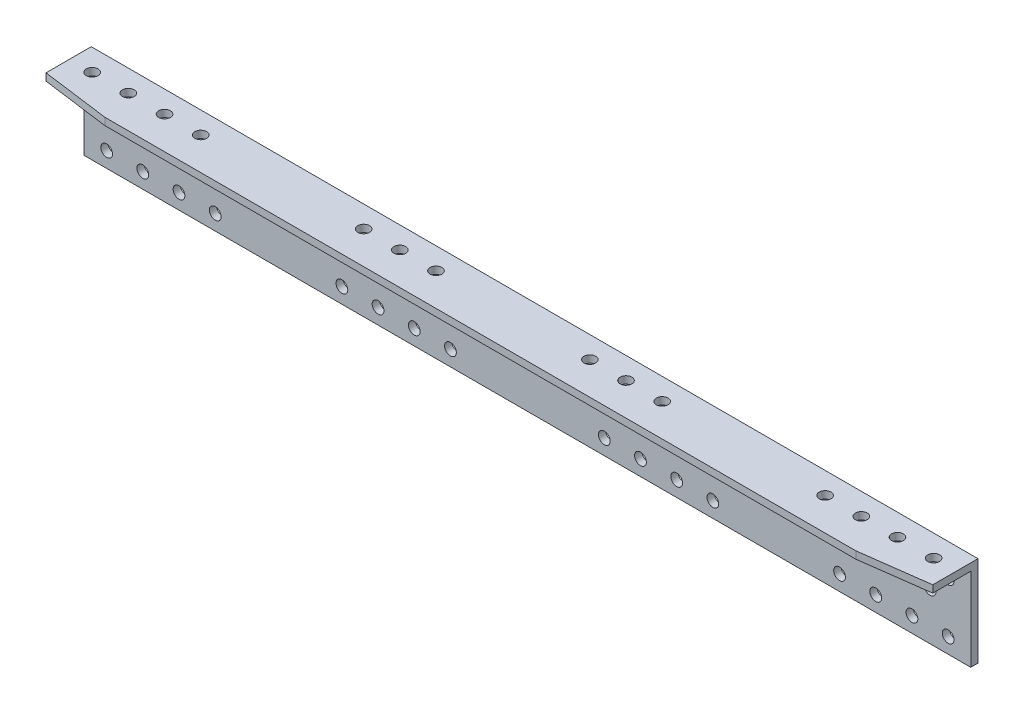
SolidWorks part; units mm, degrees
material "PW90:Mi:0:31:Ar:0:-1:Sc:1:So:2:Re:16:Ts:17:18:19:20:21:22:"
ref_plane "前视" through (0, 0, 0) normal (0, 0, 1) x (1, 0, 0)
ref_plane "上视" through (0, 0, 0) normal (0, 1, 0) x (1, 0, 0)
ref_plane "右视" through (0, 0, 0) normal (1, 0, 0) x (0, 0, -1)
sketch "草图1" plane through (0, 0, 0) normal (0, 0, 1) x (1, 0, 0)
  line L0 (0, 0) -> (0, 213.0221) construction
  line L1 (0, 213.0221) -> (0, 106) construction
  line L2 (210, 146) -> (980, 146) construction
  line L3 (-980, 200) -> (980, 200)
  line L4 (-980, 200) -> (-980, 0)
  line L5 (-980, 0) -> (980, 0)
  line L6 (980, 200) -> (980, 0)
  line L7 (143, 106) -> (370, 106) construction
  line L8 (930, 159) -> (930, 17.8164) construction
  line L9 (980, 34) -> (210, 34) construction
  line L10 (890, 175.3513) -> (890, 17.8164) construction
  line L11 (850, 159) -> (850, 17.8164) construction
  line L12 (810, 175.3513) -> (810, 17.8164) construction
  line L13 (770, 175.3513) -> (770, 17.8164) construction
  line L14 (730, 175.3513) -> (730, 17.8164) construction
  line L15 (0, 0) -> (330, 0) construction
  line L16 (0, 0) -> (1632.9772, 0) construction
  line L17 (-980, 106) -> (980, 106) construction
  line L18 (650, 175.3513) -> (650, 17.8164) construction
  line L19 (690, 175.3513) -> (690, 17.8164) construction
  line L20 (550, 175.3513) -> (550, 17.8164) construction
  line L21 (450, 293.2849) -> (450, -102.0826) construction
  line L22 (370, 293.2849) -> (370, -134.4898) construction
  line L23 (290, 293.2849) -> (290, -79.3976) construction
  line L24 (210, 293.2849) -> (210, -79.3976) construction
  line L25 (130, 293.2849) -> (130, -79.3976) construction
  line L26 (410, 320.2436) -> (410, -207.8775) construction
  circle A0 centre (930, 146) radius 13
  circle A1 centre (-890, 106) radius 13
  circle A2 centre (850, 146) radius 13
  circle A3 centre (930, 34) radius 13
  circle A4 centre (850, 34) radius 13
  circle A5 centre (-810, 106) radius 13
  circle A6 centre (770, 34) radius 13
  circle A7 centre (770, 146) radius 13
  circle A8 centre (-730, 106) radius 13
  circle A9 centre (690, 146) radius 13
  circle A10 centre (690, 34) radius 13
  circle A11 centre (-650, 106) radius 13
  circle A12 centre (170, 146) radius 13
  circle A13 centre (170, 34) radius 13
  circle A14 centre (-410, 146) radius 13
  circle A15 centre (250, 34) radius 13
  circle A16 centre (250, 146) radius 13
  circle A17 centre (-450, 106) radius 13
  circle A18 centre (330, 34) radius 13
  circle A19 centre (330, 146) radius 13
  circle A20 centre (-370, 106) radius 13
  circle A21 centre (-290, 106) radius 13
  circle A22 centre (-210, 106) radius 13
  circle A23 centre (890, 106) radius 13
  circle A24 centre (810, 106) radius 13
  circle A25 centre (650, 106) radius 13
  circle A26 centre (730, 106) radius 13
  circle A27 centre (-330, 146) radius 13
  circle A28 centre (-330, 34) radius 13
  circle A29 centre (410, 146) radius 13
  circle A30 centre (-250, 146) radius 13
  circle A31 centre (-250, 34) radius 13
  circle A32 centre (450, 106) radius 13
  circle A33 centre (-170, 34) radius 13
  circle A34 centre (-170, 146) radius 13
  circle A35 centre (370, 106) radius 13
  circle A36 centre (-690, 146) radius 13
  circle A37 centre (290, 106) radius 13
  circle A38 centre (-770, 146) radius 13
  circle A39 centre (210, 106) radius 13
  circle A40 centre (-850, 146) radius 13
  circle A41 centre (130, 106) radius 13
  circle A42 centre (-930, 146) radius 13
  circle A43 centre (-690, 34) radius 13
  circle A44 centre (-770, 34) radius 13
  circle A45 centre (-850, 34) radius 13
  circle A46 centre (-930, 34) radius 13
  circle A47 centre (-130, 106) radius 13
  circle A48 centre (410, 34) radius 13
  circle A49 centre (-410, 34) radius 13
  dimension "D12" = 26
  dimension "D16" = 26
  dimension "D18" = 26
  dimension "D25" = 26
  dimension "D1" = 200
  dimension "D2" = 1960
  dimension "D3" = 54
  dimension "D4" = 40
  dimension "D5" = 72
  dimension "D6" = 50
  dimension "D7" = 40
  dimension "D8" = 80
  dimension "D9" = 80
  dimension "D10" = 80
  dimension "D11" = 80
  dimension "D13" = 80
  dimension "D14" = 80
  dimension "D15" = 100
  dimension "D19" = 530
  dimension "D20" = 80
  dimension "D21" = 80
  dimension "D22" = 80
  dimension "D23" = 80
  dimension "D24" = 40
extrude "基体-拉伸" add sketch "草图1" along normal blind 16
sketch "草图2" plane through (0, 0, 16) normal (0, 0, 1) x (1, 0, 0)
  line L0 (0, 0) -> (0, 345.2694) construction
  line L1 (980, 0) -> (980, 200) construction
  line L2 (-980, 200) -> (980, 200)
  line L3 (-980, 200) -> (-980, 184)
  line L4 (-980, 184) -> (980, 184)
  line L5 (980, 200) -> (980, 184)
  dimension "D1" = 16
extrude "凸台-拉伸1" add sketch "草图2" along normal blind 104
sketch "草图3" plane through (0, 200, 0) normal (0, 1, 0) x (-1, 0, 0)
  line L0 (-277.803, 48) -> (-964.3408, 48) construction
  line L1 (-980, 120) -> (980, 120) construction
  line L2 (-980, 120) -> (-980, 0) construction
  line L3 (-980, 100) -> (-830, 120)
  line L4 (-277.803, 48) -> (7.9594, 48) construction
  line L5 (0, 0) -> (0, 96) construction
  line L6 (980, 100) -> (830, 120)
  line L7 (-830, 120) -> (-980, 120)
  line L8 (-980, 120) -> (-980, 100)
  line L9 (830, 120) -> (980, 120)
  line L11 (980, 120) -> (980, 100)
  circle A0 centre (-930, 48) radius 13
  circle A1 centre (-850, 48) radius 13
  circle A2 centre (-770, 48) radius 13
  circle A3 centre (-690, 48) radius 13
  circle A4 centre (-330, 48) radius 13
  circle A5 centre (-250, 48) radius 13
  circle A6 centre (-170, 48) radius 13
  circle A7 centre (170, 48) radius 13
  circle A8 centre (250, 48) radius 13
  circle A9 centre (330, 48) radius 13
  circle A10 centre (930, 48) radius 13
  circle A11 centre (850, 48) radius 13
  circle A12 centre (770, 48) radius 13
  circle A13 centre (690, 48) radius 13
  point P4 (-830, 120)
  point P5 (-980, 100)
  dimension "D5" = 26
  dimension "D1" = 72
  dimension "D2" = 150
  dimension "D3" = 20
  dimension "D4" = 50
  dimension "D6" = 80
  dimension "D7" = 80
  dimension "D8" = 80
  dimension "D9" = 360
  dimension "D10" = 80
  dimension "D11" = 80
extrude "切除-拉伸1" cut sketch "草图3" against normal through all
